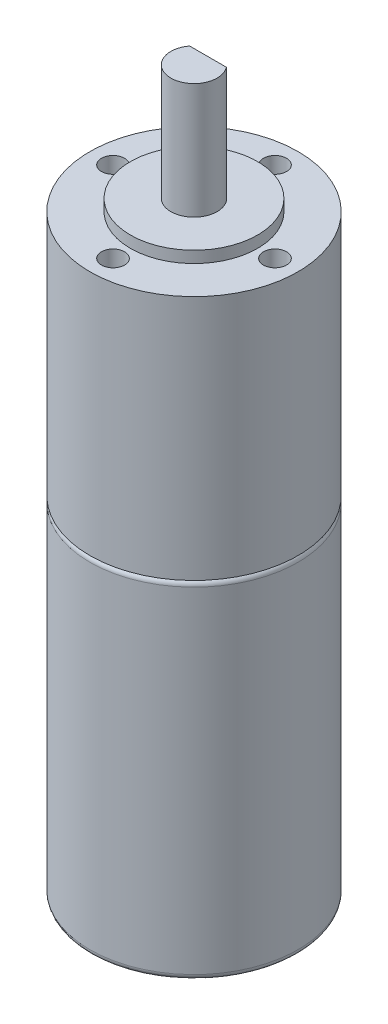
SolidWorks part; units mm, degrees
ref_plane "前视基准面" through (0, 0, 0) normal (0, 0, 1) x (1, 0, 0)
ref_plane "上视基准面" through (0, 0, 0) normal (0, 1, 0) x (1, 0, 0)
ref_plane "右视基准面" through (0, 0, 0) normal (1, 0, 0) x (0, 0, -1)
sketch "草图1" plane through (0, 0, 0) normal (0, 1, 0) x (1, 0, 0)
  circle A0 centre (0, 0) radius 18
  dimension "D1" = 36
extrude "凸台-拉伸1" add sketch "草图1" along normal blind 60
fillet "圆角1" radius 1 2 edges at (0, 0, 18) (0, 60, 18)
sketch "草图3" plane through (0, 60, 0) normal (0, 1, 0) x (1, 0, 0)
  circle A0 centre (0, 0) radius 18
  dimension "D1" = 36
extrude "凸台-拉伸2" add sketch "草图3" along normal blind 42.5
sketch "草图4" plane through (0, 102.5, 0) normal (0, 1, 0) x (1, 0, 0)
  circle A0 centre (0, 0) radius 11
  dimension "D1" = 22
extrude "凸台-拉伸3" add sketch "草图4" along normal blind 2
sketch "草图5" plane through (0, 104.5, 0) normal (0, 1, 0) x (1, 0, 0)
  circle A0 centre (0, 0) radius 4
  dimension "D1" = 8
extrude "凸台-拉伸4" add sketch "草图5" along normal blind 20
sketch "草图6" plane through (0, 124.5, 0) normal (0, 1, 0) x (1, 0, 0)
  line L0 (-3.1801, 2.4263) -> (3.1801, 2.4263)
  arc A0 (3.1801, 2.4263) -> (-3.1801, 2.4263) centre (0, 0) ccw
extrude "切除-拉伸1" cut sketch "草图6" against normal blind 15
sketch "草图7" plane through (0, 102.5, 0) normal (0, 1, 0) x (1, 0, 0)
  circle A1 centre (0, 14) radius 2
  circle A2 centre (14, 0) radius 2
  circle A3 centre (0, -14) radius 2
  circle A4 centre (-14, 0) radius 2
  point P13 (0, 0)
  dimension "D1" = 4
  dimension "D2" = 14
  dimension "D3" = 4
extrude "切除-拉伸2" cut sketch "草图7" against normal blind 5
